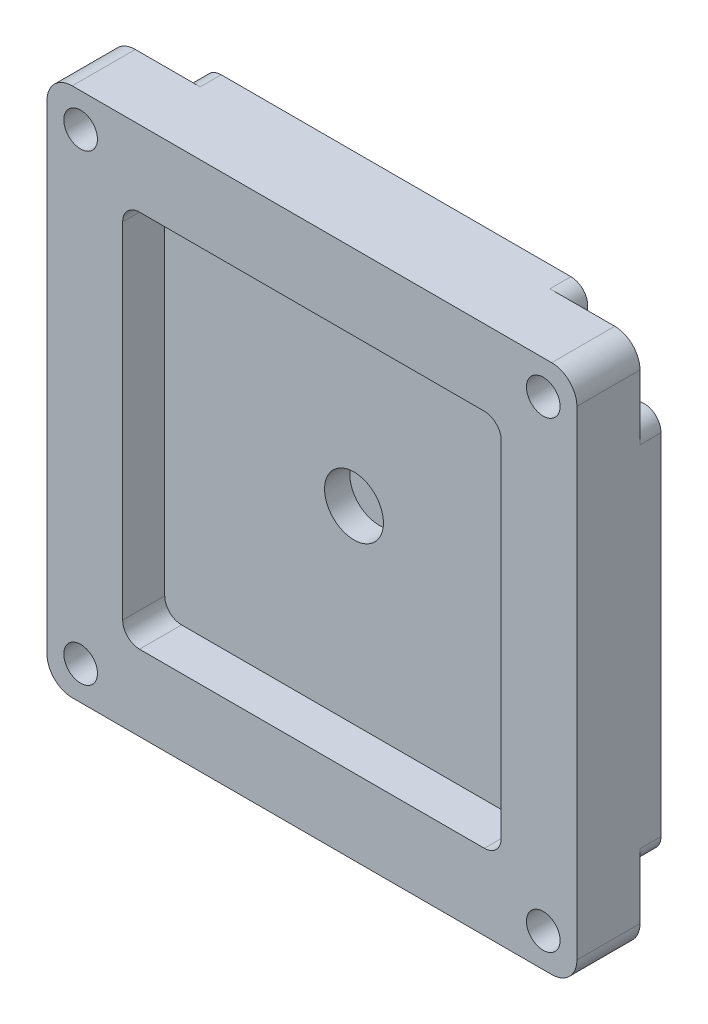
SolidWorks part; units mm, degrees
ref_plane "Front Plane" through (0, 0, 0) normal (0, 0, 1) x (1, 0, 0)
ref_plane "Top Plane" through (0, 0, 0) normal (0, 1, 0) x (1, 0, 0)
ref_plane "Right Plane" through (0, 0, 0) normal (1, 0, 0) x (0, 0, -1)
sketch "Sketch1" plane through (0, 0, 0) normal (0, 0, 1) x (1, 0, 0)
  line L5 (31.5, -31.5) -> (-31.5, -31.5)
  line L6 (31.5, -31.5) -> (31.5, 31.5)
  line L7 (31.5, 31.5) -> (-31.5, 31.5)
  line L8 (-31.5, -31.5) -> (-31.5, 31.5)
  line L9 (31.5, -31.5) -> (-31.5, 31.5) construction
  line L10 (31.5, 31.5) -> (-31.5, -31.5) construction
  circle A0 centre (-27.5, 27.5) radius 2
  circle A1 centre (27.5, 27.5) radius 2
  circle A2 centre (27.5, -27.5) radius 2
  circle A3 centre (-27.5, -27.5) radius 2
  point P0 (0, 0)
  point P18 (0, 0)
  dimension "D3" = 4
  dimension "D1" = 63
  dimension "D2" = 63
  dimension "D4" = 27.5
  dimension "D5" = 27.5
  dimension "D6" = 4
extrude "Boss-Extrude1" add sketch "Sketch1" along normal mid plane 10
ref_plane "Plane1" through (0, 0, 5) normal (0, 0, 1) x (1, 0, 0)
sketch "Sketch3" plane through (0, 0, 5) normal (0, 0, 1) x (1, 0, 0)
  line L1 (22.5, -22.5) -> (-22.5, -22.5)
  line L2 (22.5, -22.5) -> (22.5, 22.5)
  line L3 (22.5, 22.5) -> (-22.5, 22.5)
  line L4 (-22.5, -22.5) -> (-22.5, 22.5)
  line L5 (22.5, -22.5) -> (-22.5, 22.5) construction
  line L6 (22.5, 22.5) -> (-22.5, -22.5) construction
  point P0 (0, 0)
  dimension "D1" = 45
  dimension "D2" = 45
extrude "Cut-Extrude1" cut sketch "Sketch3" against normal blind 5
fillet "Fillet1" radius 3 4 edges at (-31.5, -31.5, 0) (31.5, -31.5, 0) (31.5, 31.5, 0) (-31.5, 31.5, 0)
sketch "Sketch4" plane through (0, 0, 5) normal (0, 0, 1) x (1, 0, 0)
  circle A0 centre (0, 0) radius 3.5
  dimension "D1" = 7
extrude "Cut-Extrude2" cut sketch "Sketch4" against normal blind 8
fillet "Fillet2" radius 2 4 edges at (22.5, -22.5, 2.5) (-22.5, -22.5, 2.5) (22.5, 22.5, 2.5) (-22.5, 22.5, 2.5)
ref_plane "Plane2" through (0, 0, -5) normal (0, 0, -1) x (-1, 0, 0)
sketch "Sketch5" plane through (0, 0, -5) normal (0, 0, -1) x (-1, 0, 0)
  circle A0 centre (-27.5, 27.5) radius 5
  dimension "D1" = 10
extrude "Cut-Extrude3" cut sketch "Sketch5" against normal blind 2.5
mirror "Mirror1" about plane through (0, 0, 0) normal (1, 0, 0) of "Cut-Extrude3" second plane through (0, 0, 0) second plane normal (0, 1, 0)
fillet "Fillet3" radius 2 8 edges at (24.5, 31.5, -3.75) (31.5, 24.5, -3.75) (31.5, -24.5, -3.75) (24.5, -31.5, -3.75) (-24.5, 31.5, -3.75) (-31.5, 24.5, -3.75) (-31.5, -24.5, -3.75) (-24.5, -31.5, -3.75)
